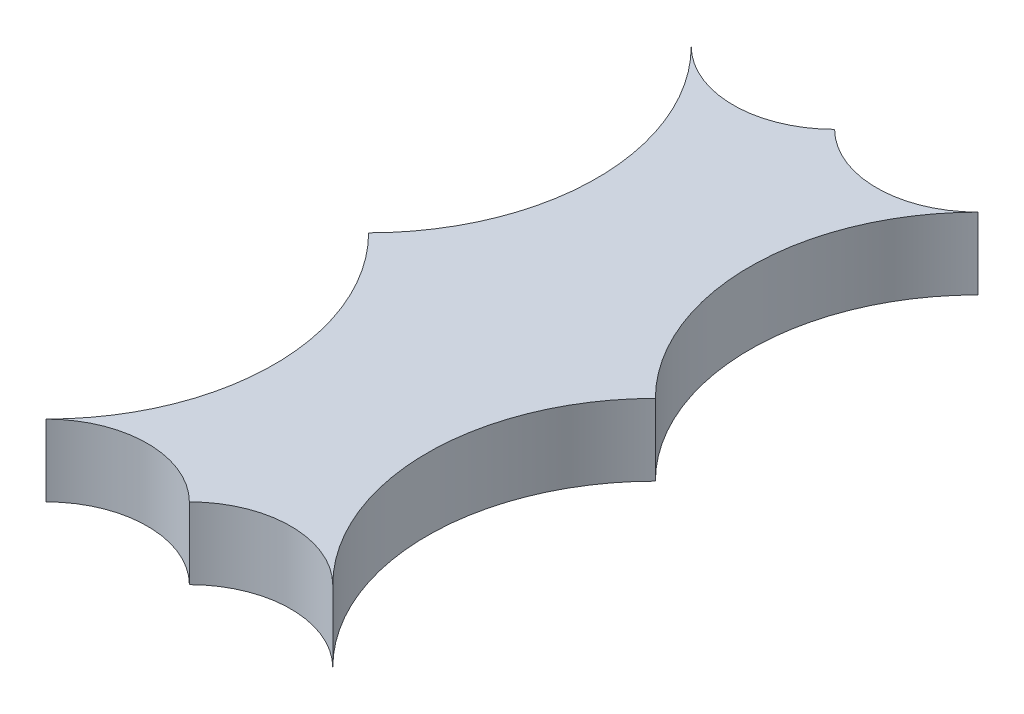
SolidWorks part; units mm, degrees
ref_plane "Front Plane" through (0, 0, 0) normal (0, 0, 1) x (1, 0, 0)
ref_plane "Top Plane" through (0, 0, 0) normal (0, 1, 0) x (1, 0, 0)
ref_plane "Right Plane" through (0, 0, 0) normal (1, 0, 0) x (0, 0, -1)
sketch "Sketch1" plane through (0, 0, 0) normal (0, 1, 0) x (1, 0, 0)
  arc A0 (21.9501, 45.2381) -> (21.9501, 27.2381) centre (12.9501, 36.2381) cw
  arc A1 (21.9501, 45.2381) -> (29.9501, 45.2381) centre (25.9501, 49.2381) ccw
  arc A2 (37.9501, 45.2381) -> (37.9501, 27.2381) centre (46.9501, 36.2381) ccw
  arc A3 (37.9501, 45.2381) -> (29.9501, 45.2381) centre (33.9501, 49.2381) cw
  arc A4 (21.9501, 9.2381) -> (29.9501, 9.2381) centre (25.9501, 5.2381) cw
  arc A5 (21.9501, 9.2381) -> (21.9501, 27.2381) centre (12.9501, 18.2381) ccw
  arc A6 (37.9501, 9.2381) -> (37.9501, 27.2381) centre (46.9501, 18.2381) cw
  arc A7 (37.9501, 9.2381) -> (29.9501, 9.2381) centre (33.9501, 5.2381) ccw
extrude "Boss-Extrude1" add sketch "Sketch1" along normal blind 4
